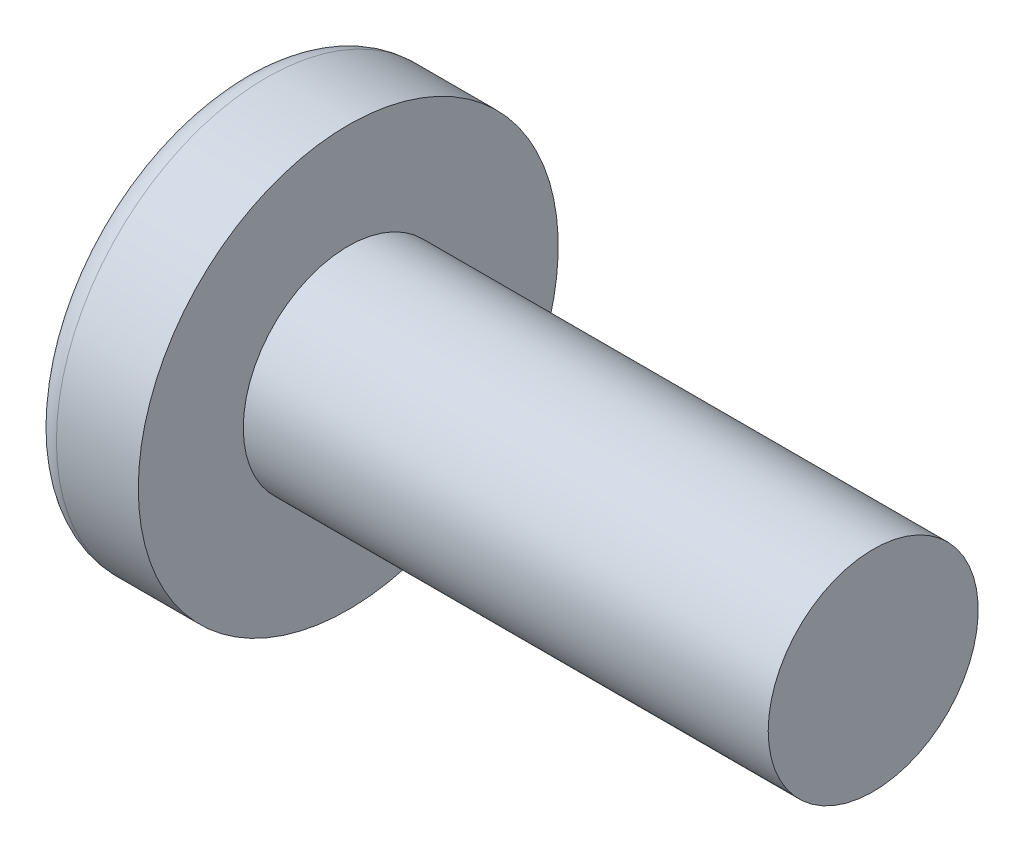
SolidWorks part; units mm, degrees
ref_plane "Plane1" through (0, 0, 0) normal (0, 0, 1) x (1, 0, 0)
ref_plane "Plane2" through (0, 0, 0) normal (0, 1, 0) x (1, 0, 0)
ref_plane "Plane3" through (0, 0, 0) normal (1, 0, 0) x (0, 0, -1)
sketch "BodySke" plane through (0, 0, 0) normal (0, 0, 1) x (1, 0, 0)
  line L0 (1.6, 1) -> (1.6, 2)
  line L1 (2, 6.35) -> (2, -3.175) construction
  line L2 (-25.4, 0) -> (127, 0) construction
  line L3 (6.6, 0) -> (0, 0)
  line L4 (1.6, 1) -> (6.6, 1)
  line L5 (6.6, 1) -> (6.6, 0)
  line L6 (0.8201, 2) -> (1.6, 2)
  line L7 (1.6, -1) -> (6.6, -1) construction
  line L8 (1.6, 6.35) -> (1.6, -3.175) construction
  arc A0 (0.6271, 1.9027) -> (0, 0) centre (3.2, 0) ccw
  arc A2 (0.6271, 1.9027) -> (0.8201, 2) centre (0.8201, 1.76) cw
  dimension "Head_crown_rad" = 3.2
  dimension "Head_fillet_rad" = 0.24
  dimension "Diameter" = 2
  dimension "Length" = 5
  dimension "Head_ht" = 1.6
  dimension "Head_dia" = 4
  dimension "Advance" = 0.4
  dimension "Thread_nom" = 5
revolve "Base-Revolve" add sketch "BodySke" angle 360 about L2
cosmetic thread "ThreadCosmetic" [suppressed] parameters "Thread_length"=4.6, "Thread_minor"=1.548
sketch "Sketch3" plane through (0, 0, 0) normal (1, 0, 0) x (0, 0, -1)
  line L0 (0.24, -0.91) -> (-0.24, -0.91)
  line L1 (0.24, -0.91) -> (0.24, 0.91)
  line L2 (-0.24, 0.91) -> (0.24, 0.91)
  line L3 (-0.24, 0.91) -> (-0.24, -0.91)
  dimension "Cross_dia" = 1.82
  dimension "D1" = 0.91
  dimension "Cross_width" = 0.48
  dimension "D2" = 0.24
ref_plane "Plane4" through (1.19, 0, 0) normal (1, 0, 0) x (0, 0, -1)
sketch "Sketch4" plane through (1.19, 0, 0) normal (1, 0, 0) x (0, 0, -1)
  line L0 (0.12, -0.12) -> (-0.12, -0.12)
  line L1 (0.12, -0.12) -> (0.12, 0.12)
  line L2 (-0.12, 0.12) -> (0.12, 0.12)
  line L3 (-0.12, 0.12) -> (-0.12, -0.12)
  dimension "D2" = 0.24
  dimension "D1" = 0.24
  dimension "D3" = 0.12
  dimension "D4" = 0.12
loft "Cut-Loft1" cut profiles "Sketch3", "Sketch4"
pattern_circular "CirPattern1" count 2 every 90 about axis through (0, 0, 0) along (1, 0, 0) of "Cut-Loft1"
sketch "ThdSchSke" plane through (0, 0, 0) normal (0, 0, 1) x (1, 0, 0)
  line L0 (2, -0.774) -> (1.8418, -1)
  line L1 (2, -0.774) -> (2.1582, -1)
  line L2 (2.1582, -1) -> (2.1582, -1.25)
  line L3 (-3.175, 0) -> (5.1513, 0) construction
  line L5 (2.1582, -1.25) -> (1.8418, -1.25)
  line L6 (1.8418, -1.25) -> (1.8418, -1)
  dimension "Diameter" = 2
  dimension "SideAngle" = 55
  dimension "VeeAngle" = 70
  dimension "Thread_minor" = 1.548
  dimension "Overcut" = 2.5
  dimension "Start" = 2
revolve "ThreadSchematic" [suppressed] cut sketch "ThdSchSke" angle 360 about L3
pattern_linear "ThdSchPat" [suppressed]
equation "\"D1@Sketch3\" = \"Cross_dia@Sketch3\" / 2"
equation "\"D2@Sketch3\" = \"Cross_width@Sketch3\" / 2"
equation "\"D1@Sketch4\" = \"Cross_width@Sketch3\" *.5"
equation "\"D2@Sketch4\" = \"D1@Sketch4\""
equation "\"D3@Sketch4\" = \"D1@Sketch4\" / 2"
equation "\"D4@Sketch4\" = \"D2@Sketch4\" / 2"
equation "\"Thread_length@ThreadCosmetic\" = ((sgn( (\"Length@BodySke\" - \"Advance@BodySke\" ) - \"Thread_nom@BodySke\" )-1)*( (\"Length@BodySke\" - \"Advance@BodySke\" ) - \"Thread_nom@BodySke\" ))/-2+ \"Thread_nom@BodySke\""
equation "\"Thread_minor@ThdSchSke\" = \"Thread_minor@ThreadCosmetic\""
equation "\"Diameter@ThdSchSke\" = \"Diameter@BodySke\""
equation "\"Overcut@ThdSchSke\" = \"Diameter@BodySke\" * 1.25"
equation "\"Start@ThdSchSke\" = \"Head_ht@BodySke\" + \"Length@BodySke\" - \"Thread_length@ThreadCosmetic\"  '---Non-countersunk---"
equation "\"Num_threads@ThdSchPat\" = int( \"Thread_length@ThreadCosmetic\" / \"Advance@BodySke\" + 0.999 )  + 1"
equation "\"Advance@ThdSchPat\" = \"Thread_length@ThreadCosmetic\" /  (\"Num_threads@ThdSchPat\" - 1) 'relax it"
